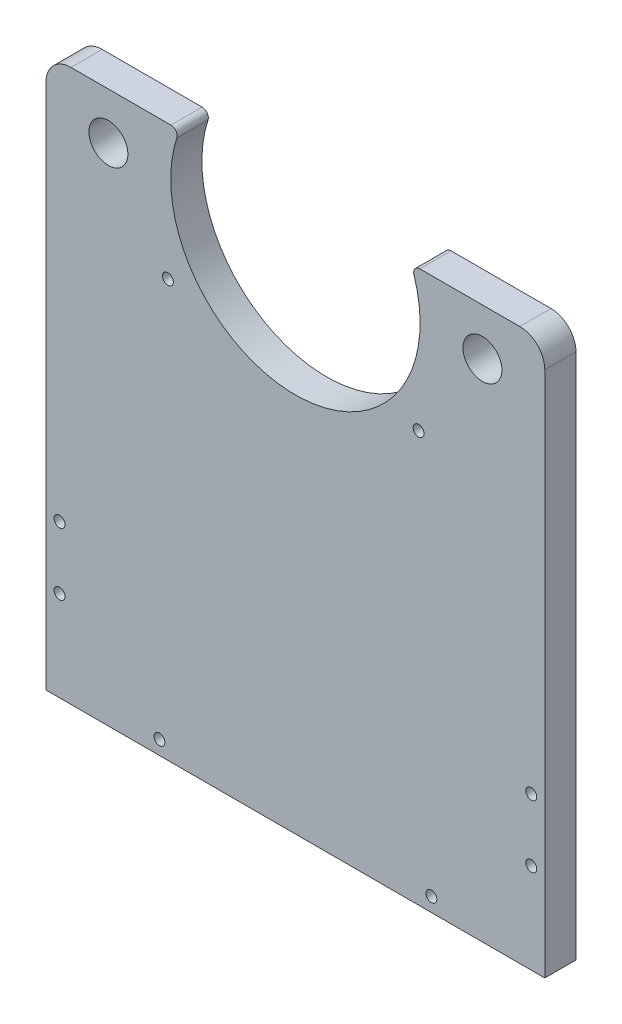
SolidWorks part; units mm, degrees
ref_plane "Front Plane" through (0, 0, 0) normal (0, 0, 1) x (1, 0, 0)
ref_plane "Top Plane" through (0, 0, 0) normal (0, 1, 0) x (1, 0, 0)
ref_plane "Right Plane" through (0, 0, 0) normal (1, 0, 0) x (0, 0, -1)
sketch "Sketch1" plane through (0, 0, 0) normal (0, 0, 1) x (1, 0, 0)
  line L0 (80, 162) -> (80, 137.2793) construction
  line L1 (0, 0) -> (40, 0)
  line L2 (0, 0) -> (0, 169)
  line L3 (8, 177) -> (40, 177)
  line L5 (20, 177) -> (20, 162) construction
  line L6 (40, 177) -> (40.0625, 177)
  line L7 (40, 162) -> (0, 162) construction
  line L8 (160, 0) -> (120, 0)
  line L13 (160, 0) -> (160, 169)
  line L15 (152, 177) -> (120, 177)
  line L16 (40, 0) -> (120, 0)
  line L17 (119.9375, 177) -> (120, 177)
  arc A0 (0, 169) -> (8, 177) centre (8, 169) cw
  circle A2 centre (20, 162) radius 6.25
  circle A4 centre (140, 162) radius 6.25
  arc A5 (160, 169) -> (152, 177) centre (152, 169) ccw
  circle A6 centre (4.3284, 49) radius 1.75
  circle A7 centre (4.3284, 29) radius 1.75
  circle A10 centre (36.3713, 4.5) radius 1.75
  circle A12 centre (123.6287, 4.5) radius 1.75
  circle A13 centre (155.6716, 29) radius 1.75
  circle A14 centre (155.6716, 49) radius 1.75
  arc A15 (41.9643, 174.381) -> (118.0357, 174.381) centre (80, 162) ccw
  arc A16 (118.0357, 174.381) -> (119.9375, 177) centre (119.9375, 175) cw
  arc A17 (41.9643, 174.381) -> (40.0625, 177) centre (40.0625, 175) ccw
  point P7 (0, 177)
  point P40 (117.081, 177)
  dimension "D3" = 8
  dimension "D4" = 12.5
  dimension "D5" = 60
  dimension "D8" = 2
  dimension "D1" = 160
  dimension "D2" = 177
extrude "Boss-Extrude1" add sketch "Sketch1" along normal blind 10
sketch "Sketch11" plane through (0, 0, 0) normal (0, 0, -1) x (-1, 0, 0)
  circle A3 centre (-119.5154, 131.812) radius 1.75
  circle A4 centre (-39.0786, 133.7472) radius 1.75
extrude "Cut-Extrude2" cut sketch "Sketch11" against normal blind 10
